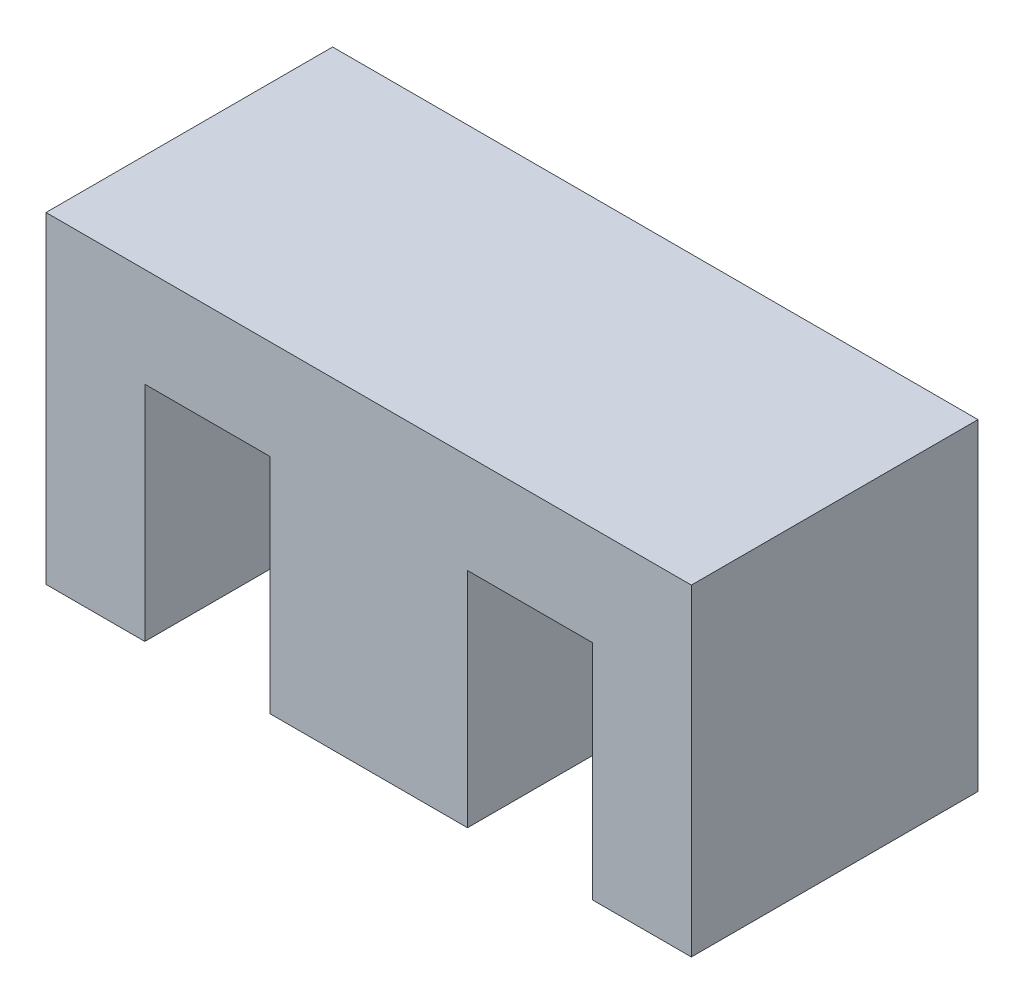
SolidWorks part; units mm, degrees
ref_plane "Ön Düzlem" through (0, 0, 0) normal (0, 0, 1) x (1, 0, 0)
ref_plane "Üst Düzlem" through (0, 0, 0) normal (0, 1, 0) x (1, 0, 0)
ref_plane "Sağ Düzlem" through (0, 0, 0) normal (1, 0, 0) x (0, 0, -1)
sketch "Sketch2" plane through (0, 0, 0) normal (0, 0, 1) x (1, 0, 0)
  line L0 (-23.2202, -35.0641) -> (-23.2202, -54.2241)
  line L1 (-70.2202, -26.5241) -> (-14.7202, -26.5241)
  line L2 (-70.2202, -26.5241) -> (-70.2202, -54.2241)
  line L3 (-70.2202, -54.2241) -> (-61.7202, -54.2241)
  line L4 (-14.7202, -26.5241) -> (-14.7202, -54.2241)
  line L5 (-61.7202, -35.0641) -> (-61.7202, -54.2241)
  line L6 (-61.7202, -35.0641) -> (-50.9702, -35.0641)
  line L7 (-50.9702, -54.2241) -> (-33.9702, -54.2241)
  line L8 (-33.9702, -35.0641) -> (-33.9702, -54.2241)
  line L9 (-50.9702, -35.0641) -> (-50.9702, -54.2241)
  line L10 (-23.2202, -54.2241) -> (-14.7202, -54.2241)
  line L11 (-33.9702, -35.0641) -> (-23.2202, -35.0641)
extrude "Extrude2" add sketch "Sketch2" along normal blind 24.65
